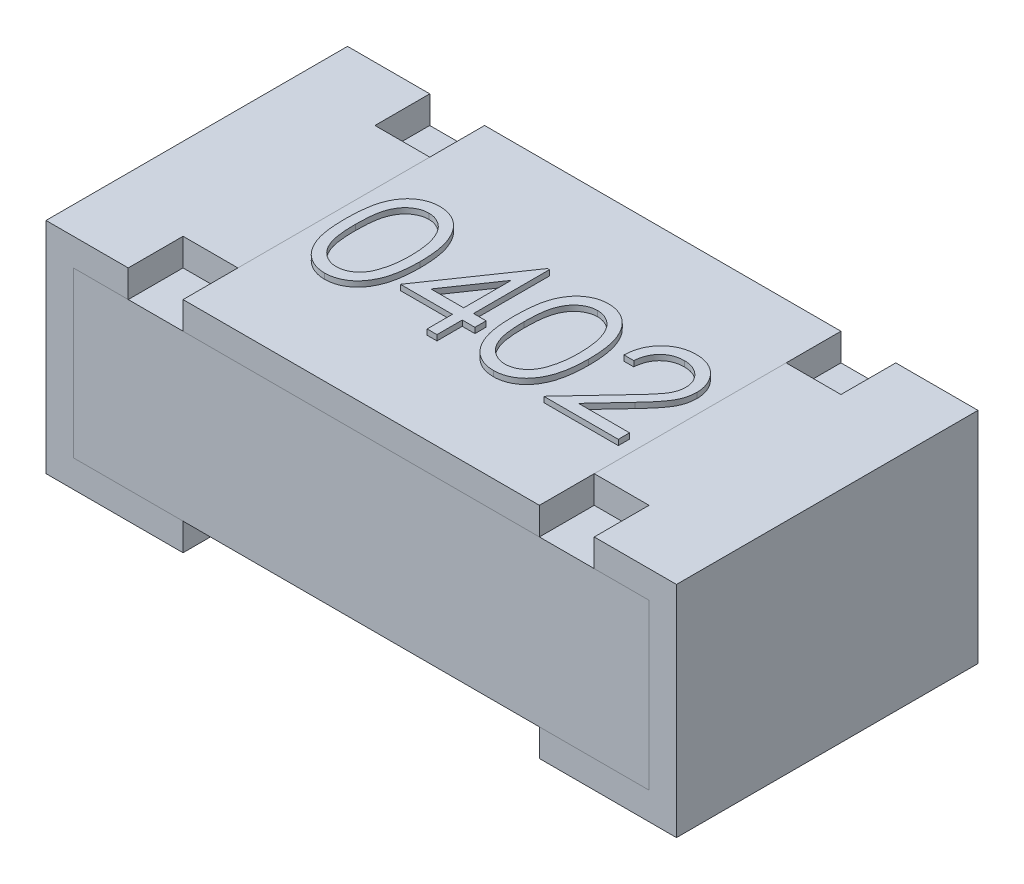
SolidWorks part; units mm, degrees
ref_plane "Front Plane" through (0, 0, 0) normal (0, 0, 1) x (1, 0, 0)
ref_plane "Top Plane" through (0, 0, 0) normal (0, 1, 0) x (1, 0, 0)
ref_plane "Right Plane" through (0, 0, 0) normal (1, 0, 0) x (0, 0, -1)
sketch "Croquis1" plane through (0, 0, 0) normal (0, 1, 0) x (1, 0, 0)
  line L1 (0.525, 0.275) -> (-0.525, 0.275)
  line L2 (0.525, 0.275) -> (0.525, -0.275)
  line L3 (0.525, -0.275) -> (-0.525, -0.275)
  line L4 (-0.525, 0.275) -> (-0.525, -0.275)
  line L5 (0.525, 0.275) -> (-0.525, -0.275) construction
  line L6 (0.525, -0.275) -> (-0.525, 0.275) construction
  point P0 (0, 0)
  dimension "D1" = 0.55
  dimension "D2" = 1.05
extrude "Extruir1" add sketch "Croquis1" along normal blind 0.35
sketch "Croquis2" plane through (0, 0, 0.275) normal (0, 0, 1) x (1, 0, 0)
  line L0 (0.525, 0.35) -> (0.525, 0) construction
  line L1 (-0.525, 0) -> (0.525, 0)
  line L2 (-0.525, 0) -> (-0.525, 0.05)
  line L3 (-0.525, 0.05) -> (0.525, 0.05)
  line L4 (0.525, 0) -> (0.525, 0.05)
  dimension "D1" = 0.05
extrude "Extruir2" cut sketch "Croquis2" against normal through all
sketch "Croquis3" plane through (0, 0, 0.275) normal (0, 0, 1) x (1, 0, 0)
  line L0 (-0.325, 0.4) -> (-0.575, 0.4)
  line L1 (-0.575, 0.4) -> (-0.575, 0)
  line L2 (-0.575, 0) -> (-0.325, 0)
  line L4 (-0.525, 0.35) -> (-0.525, 0.05) construction
  line L5 (-0.525, 0.35) -> (0.525, 0.35) construction
  dimension "D1" = 0.05
  dimension "D2" = 0.05
  dimension "D3" = 0.25
  dimension "D4" = 0.25
  dimension "D5" = 0.4
sketch3d "Croquis3D1"
  line L0 (-0.325, 0.4, 0.275) -> (-0.325, 0.4, -0.275)
  line L1 (-0.325, 0.4, -0.275) -> (-0.325, 0.35, -0.275)
  line L2 (-0.325, 0.35, -0.275) -> (-0.325, 0.35, 0.275)
  line L3 (-0.325, 0.35, 0.275) -> (-0.325, 0.4, 0.275)
  line L4 (-0.525, 0.35, -0.275) -> (-0.525, 0.35, 0.275) construction
  dimension "D1" = 0.25
sweep "Barrer1" add profiles "Croquis3D1" path "Croquis3"
ref_plane "Plano1" through (0, 0.35, 0.275) normal (1, 0, 0) x (0, 0, -1)
mirror "Simetría1" about plane through (0, 0.35, 0.275) normal (1, 0, 0) of bodies 104
sketch "Croquis4" plane through (-0.325, 0, 0) normal (1, 0, 0) x (0, 0, -1)
  line L1 (-0.275, 0.4) -> (0.275, 0.4)
  line L2 (-0.275, 0.4) -> (-0.275, 0.35)
  line L3 (-0.275, 0.35) -> (0.275, 0.35)
  line L4 (0.275, 0.4) -> (0.275, 0.35)
extrude "Extruir3" add sketch "Croquis4" along normal up to surface (0.65 mm away) separate body up to face at (0.325, 0.375, 0)
sketch "Croquis5" plane through (0, 0.4, 0) normal (0, 1, 0) x (1, 0, 0)
  line L0 (0, -0.275) -> (0, 0.275) construction
  line L1 (-0.325, -0.275) -> (-0.425, -0.275)
  line L2 (-0.325, -0.275) -> (-0.325, -0.175)
  line L3 (-0.325, -0.175) -> (-0.425, -0.175)
  line L4 (-0.425, -0.275) -> (-0.425, -0.175)
  line L5 (0.325, -0.275) -> (-0.325, -0.275) construction
  line L6 (0.325, 0.275) -> (-0.325, 0.275) construction
  line L7 (-0.325, 0) -> (0.325, 0) construction
  line L8 (-0.325, 0.275) -> (-0.325, -0.275) construction
  line L9 (0.325, 0.275) -> (0.325, -0.275) construction
  line L10 (-0.425, 0.275) -> (-0.425, 0.175)
  line L11 (-0.325, 0.175) -> (-0.425, 0.175)
  line L12 (-0.325, 0.275) -> (-0.325, 0.175)
  line L13 (-0.325, 0.275) -> (-0.425, 0.275)
  line L14 (0.325, 0.275) -> (0.425, 0.275)
  line L15 (0.325, 0.275) -> (0.325, 0.175)
  line L16 (0.325, 0.175) -> (0.425, 0.175)
  line L17 (0.425, 0.275) -> (0.425, 0.175)
  line L18 (0.425, -0.275) -> (0.425, -0.175)
  line L19 (0.325, -0.175) -> (0.425, -0.175)
  line L20 (0.325, -0.275) -> (0.325, -0.175)
  line L21 (0.325, -0.275) -> (0.425, -0.275)
  dimension "D1" = 0.1
  dimension "D2" = 0.1
extrude "Extruir4" cut sketch "Croquis5" against normal up to next (0.05 mm away)
sketch "Sketch1" plane through (0, 0.4, 0) normal (0, 1, 0) x (1, 0, 0)
  text T0 "0402" font "Century Gothic" height 0.2
extrude "Boss-Extrude1" add sketch "Sketch1" along normal blind 0.01
